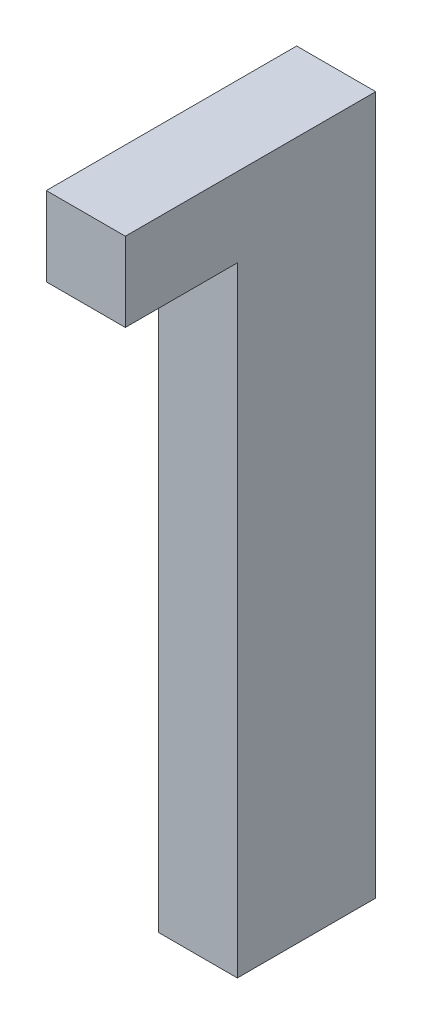
SolidWorks part; units mm, degrees
ref_plane "Front Plane" through (0, 0, 0) normal (0, 0, 1) x (1, 0, 0)
ref_plane "Top Plane" through (0, 0, 0) normal (0, 1, 0) x (1, 0, 0)
ref_plane "Right Plane" through (0, 0, 0) normal (1, 0, 0) x (0, 0, -1)
sketch "Sketch1" plane through (0, 0, 0) normal (0, 1, 0) x (1, 0, 0)
  line L1 (-25.12, 219.6778) -> (51.08, 219.6778)
  line L2 (-25.12, 219.6778) -> (-25.12, -21.6222)
  line L3 (-25.12, -21.6222) -> (51.08, -21.6222)
  line L4 (51.08, 219.6778) -> (51.08, -21.6222)
extrude "Boss-Extrude2" add sketch "Sketch1" along normal blind 673.1
sketch "Sketch3" plane through (51.08, 0, 0) normal (1, 0, 0) x (0, 0, -1)
  line L0 (-21.6222, 673.1) -> (-21.6222, 0) construction
  line L1 (-21.6222, 596.9) -> (86.3278, 596.9)
  line L2 (-21.6222, 596.9) -> (-21.6222, 0)
  line L3 (-21.6222, 0) -> (86.3278, 0)
  line L4 (86.3278, 596.9) -> (86.3278, 0)
  line L5 (41.91, 0) -> (-41.91, 0) construction
extrude "Cut-Extrude1" cut sketch "Sketch3" against normal blind 127
